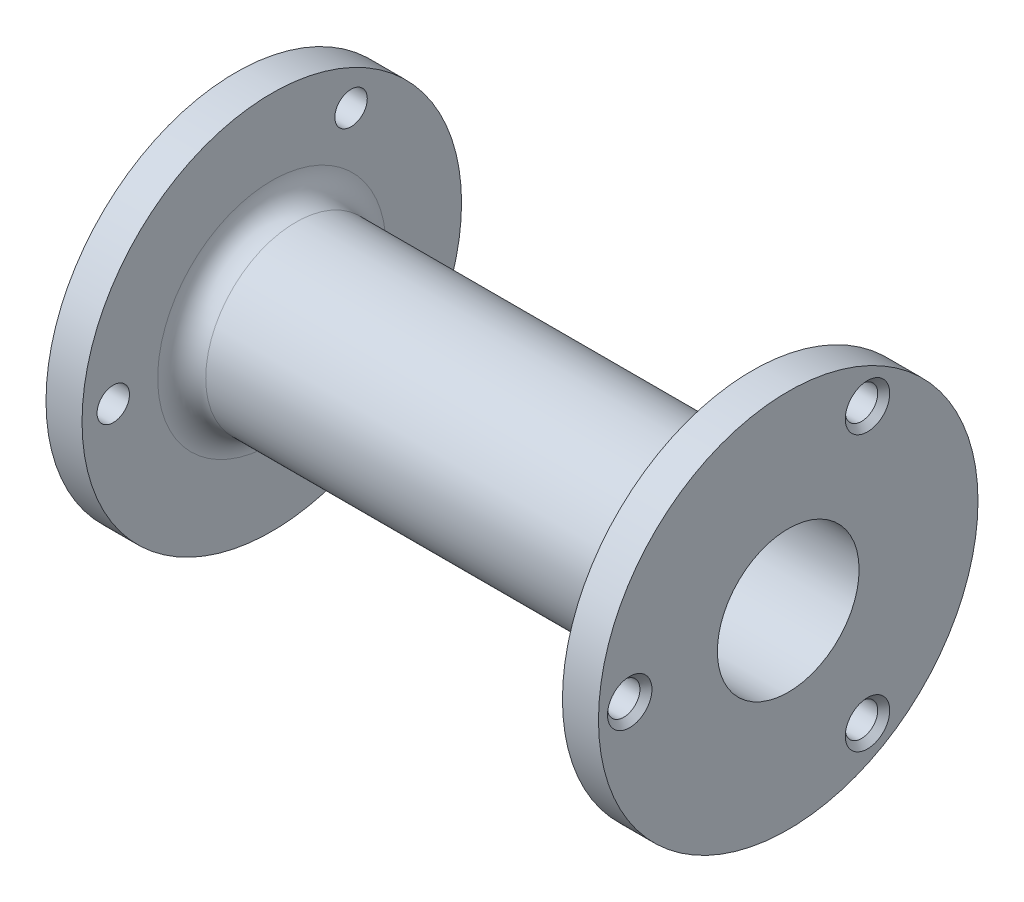
SolidWorks part; units mm, degrees
ref_plane "Front Plane" through (0, 0, 0) normal (0, 0, 1) x (1, 0, 0)
ref_plane "Top Plane" through (0, 0, 0) normal (0, 1, 0) x (1, 0, 0)
ref_plane "Right Plane" through (0, 0, 0) normal (1, 0, 0) x (0, 0, -1)
sketch "Sketch1" plane through (0, 0, 0) normal (0, 0, 1) x (1, 0, 0)
  line L0 (0, 5.9) -> (0, 15.8)
  line L1 (0, 0) -> (-13.4865, 0) construction
  line L2 (0, 15.8) -> (3, 15.8)
  line L3 (3, 15.8) -> (3, 9.5)
  line L4 (3, 5.9) -> (43, 5.9)
  line L5 (5, 7.5) -> (41, 7.5)
  line L6 (3, 5.9) -> (0, 5.9)
  line L7 (43, 9.5) -> (43, 15.8)
  line L8 (43, 15.8) -> (46, 15.8)
  line L9 (46, 15.8) -> (46, 5.9)
  line L10 (46, 5.9) -> (43, 5.9)
  arc A0 (41, 7.5) -> (43, 9.5) centre (41, 9.5) ccw
  arc A1 (5, 7.5) -> (3, 9.5) centre (5, 9.5) cw
  point P17 (3, 7.5)
  dimension "D1" = 11.8
  dimension "D2" = 3
  dimension "D6" = 2
  dimension "D3" = 31.6
  dimension "D4" = 1.6
  dimension "D5" = 40
revolve "Revolve1" add sketch "Sketch1" angle 360 about L1
sketch "Sketch3" plane through (46, 0, 0) normal (1, 0, 0) x (0, 0, -1)
  line L0 (-13.2, 0) -> (0, 0) construction
  circle A0 centre (-13.2, 0) radius 1.35
  circle A1 centre (0, 0) radius 15.8 construction
  circle A3 centre (6.6, 11.4315) radius 1.35
  circle A4 centre (6.6, -11.4315) radius 1.35
  point P4 (-15.8, 0)
  point P13 (0, 0)
  dimension "D1" = 13.2
  dimension "D2" = 2.7
  dimension "D3" = 3
extrude "Cut-Extrude1" cut sketch "Sketch3" against normal through all
chamfer "Chamfer1" distance 0.5 angle 45 6 edges at (46, 0, 11.85) (46, -11.4315, -7.95) (46, 11.4315, -7.95) (0, -11.4315, -7.95) (0, 11.4315, -7.95) (0, 0, 11.85)
